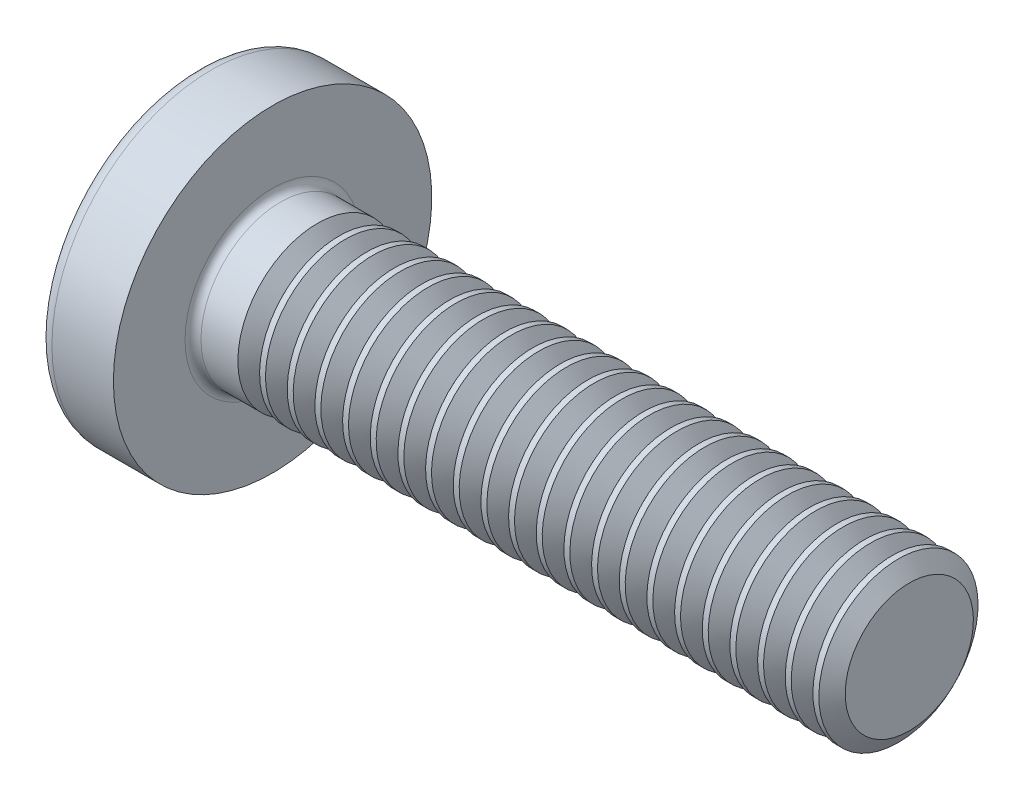
SolidWorks part; units mm, degrees
ref_plane "Plane1" through (0, 0, 0) normal (0, 0, 1) x (1, 0, 0)
ref_plane "Plane2" through (0, 0, 0) normal (0, 1, 0) x (1, 0, 0)
ref_plane "Plane3" through (0, 0, 0) normal (1, 0, 0) x (0, 0, -1)
sketch "BodySke" plane through (0, 0, 0) normal (0, 0, 1) x (1, 0, 0)
  line L0 (3.1, 2) -> (3.1, 4)
  line L1 (3.45, 6.35) -> (3.45, -3.175) construction
  line L2 (-25.4, 0) -> (127, 0) construction
  line L3 (19.1, 0) -> (0, 0)
  line L4 (3.1, 2) -> (19.1, 2)
  line L5 (19.1, 2) -> (19.1, 0)
  line L6 (1.5553, 4) -> (3.1, 4)
  line L8 (3.1, 6.35) -> (3.1, -3.175) construction
  arc A0 (1.2654, 3.8534) -> (0, 0) centre (6.5, 0) ccw
  arc A2 (1.2654, 3.8534) -> (1.5553, 4) centre (1.5553, 3.64) cw
  dimension "Head_crown_rad" = 6.5
  dimension "Head_fillet_rad" = 0.36
  dimension "Length" = 16
  dimension "Head_ht" = 3.1
  dimension "Head_dia" = 8
  dimension "Advance" = 0.7
  dimension "Thread_nom" = 16
  dimension "Diameter" = 4
revolve "Base-Revolve" add sketch "BodySke"
cosmetic thread "ThreadCosmetic" [suppressed]
fillet "Fillet1" radius 0.2 1 edges at (3.1, 0, 2)
sketch "Sketch3" plane through (0, 0, 0) normal (1, 0, 0) x (0, 0, -1)
  line L0 (0.515, -2.15) -> (-0.515, -2.15)
  line L1 (0.515, -2.15) -> (0.515, 2.15)
  line L2 (-0.515, 2.15) -> (0.515, 2.15)
  line L3 (-0.515, 2.15) -> (-0.515, -2.15)
  dimension "Cross_dia" = 4.3
  dimension "D1" = 2.15
  dimension "Cross_width" = 1.03
  dimension "D2" = 0.515
ref_plane "Plane4" through (2.34, 0, 0) normal (1, 0, 0) x (0, 0, -1)
sketch "Sketch4" plane through (2.34, 0, 0) normal (1, 0, 0) x (0, 0, -1)
  line L0 (0.515, -0.9833) -> (-0.515, -0.9833)
  line L1 (0.515, -0.9833) -> (0.515, 0.9833)
  line L2 (-0.515, 0.9833) -> (0.515, 0.9833)
  line L3 (-0.515, 0.9833) -> (-0.515, -0.9833)
  dimension "D1" = 1.03
  dimension "D2" = 1.9666
  dimension "D3" = 0.515
  dimension "D4" = 0.9833
loft "Recess" cut profiles "Sketch3", "Sketch4"
pattern_circular "RecPat" count 2 every 90 about axis through (0, 0, 0) along (1, 0, 0) of "Recess"
sketch "RecCorSke" plane through (0, 0, 0) normal (0, 0, 1) x (1, 0, 0)
  line L0 (-3.175, 0) -> (15.875, 0) construction
  line L1 (-25.4, 0) -> (127, 0) construction
  line L2 (0, 0) -> (0, 1.0146)
  line L3 (0, 1.0146) -> (2.34, 0.851)
  line L4 (2.34, 0.851) -> (2.6165, 0)
  line L5 (2.6165, 0) -> (0, 0)
  dimension "Diameter" = 1.702
  dimension "Depth" = 2.34
  dimension "Draft_angle" = 4
  dimension "Bottom_angle" = 18
revolve "RecessCore" cut sketch "RecCorSke" angle 360 about L0
sketch "ThdSchSke" plane through (0, 0, 0) normal (0, 0, 1) x (1, 0, 0)
  line L0 (4.5, -1.61) -> (4.2269, -2)
  line L1 (4.5, -1.61) -> (4.7731, -2)
  line L2 (4.7731, -2) -> (4.7731, -2.5)
  line L3 (-3.175, 0) -> (5.1513, 0) construction
  line L5 (4.7731, -2.5) -> (4.2269, -2.5)
  line L6 (4.2269, -2.5) -> (4.2269, -2)
  dimension "Diameter" = 4
  dimension "SideAngle" = 55
  dimension "VeeAngle" = 70
  dimension "Thread_minor" = 3.22
  dimension "Overcut" = 5
  dimension "Start" = 4.5
revolve "ThreadSchematic" cut sketch "ThdSchSke" angle 360 about L3
pattern_linear "ThdSchPat" count 22 spacing 0.6952 along (1, 0, 0) of "ThreadSchematic"
equation "\"D1@Sketch3\" = \"Cross_dia@Sketch3\" / 2"
equation "\"D2@Sketch3\" = \"Cross_width@Sketch3\" / 2"
equation "\"Depth@RecCorSke\" = \"Cross_depth@Plane4\""
equation "\"D1@Sketch4\" = \"Cross_width@Sketch3\""
equation "\"D2@Sketch4\" = \"Cross_dia@Sketch3\" - 2.0 * \"Cross_depth@Plane4\" * tan(26.5  * 0.017453292)"
equation "\"D3@Sketch4\" = \"D1@Sketch4\" / 2"
equation "\"D4@Sketch4\" = \"D2@Sketch4\" / 2"
equation "\"Thread_length@ThreadCosmetic\" = ((sgn( (\"Length@BodySke\" - \"Advance@BodySke\" * 2.0 ) - \"Thread_nom@BodySke\" )-1)*( (\"Length@BodySke\" - \"Advance@BodySke\" * 2.0 ) - \"Thread_nom@BodySke\" ))/-2+ \"Thread_nom@BodySke\""
equation "\"Thread_minor@ThdSchSke\" = \"Thread_minor@ThreadCosmetic\""
equation "\"Diameter@ThdSchSke\" = \"Diameter@BodySke\""
equation "\"Overcut@ThdSchSke\" = \"Diameter@BodySke\" * 1.25"
equation "\"Start@ThdSchSke\" = \"Head_ht@BodySke\" + \"Length@BodySke\" - \"Thread_length@ThreadCosmetic\"  '---Non-countersunk---"
equation "\"Num_threads@ThdSchPat\" = int( \"Thread_length@ThreadCosmetic\" / \"Advance@BodySke\" + 0.999 )  + 1"
equation "\"Advance@ThdSchPat\" = \"Thread_length@ThreadCosmetic\" /  (\"Num_threads@ThdSchPat\" - 1) 'relax it"
